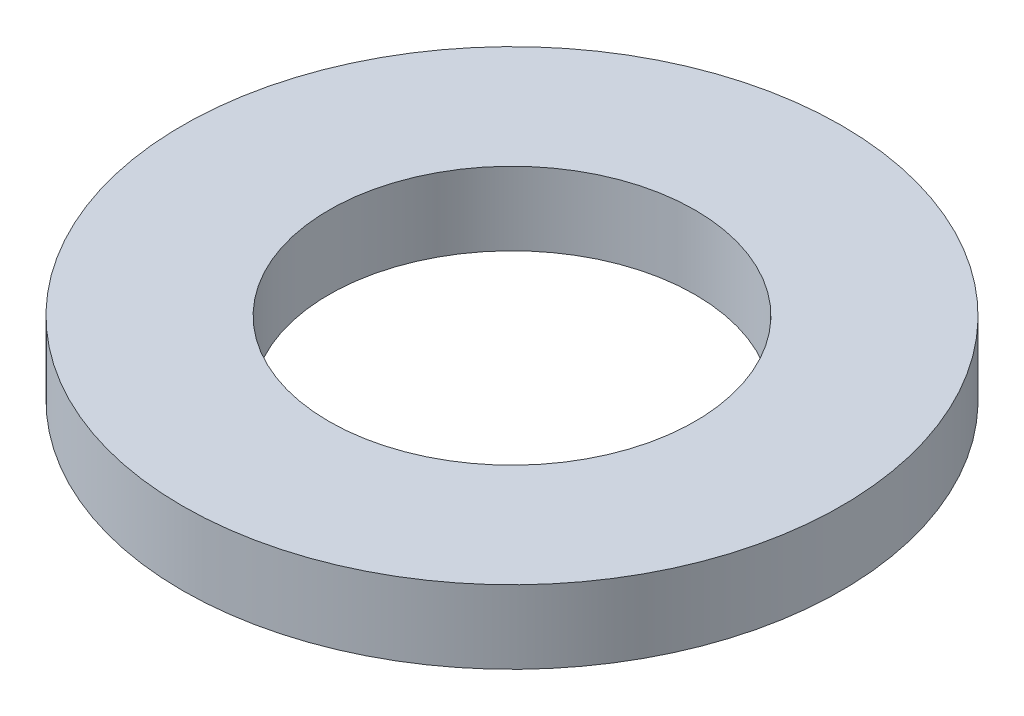
SolidWorks part; units mm, degrees
ref_plane "Front Plane" through (0, 0, 0) normal (0, 0, 1) x (1, 0, 0)
ref_plane "Top Plane" through (0, 0, 0) normal (0, 1, 0) x (1, 0, 0)
ref_plane "Right Plane" through (0, 0, 0) normal (1, 0, 0) x (0, 0, -1)
sketch "Sketch1" plane through (0, 0, 0) normal (0, 1, 0) x (1, 0, 0)
  circle A0 centre (0, 0) radius 4.5
  circle A1 centre (0, 0) radius 2.5
  dimension "D1" = 9
  dimension "D2" = 5
extrude "Boss-Extrude1" add sketch "Sketch1" along normal blind 1
